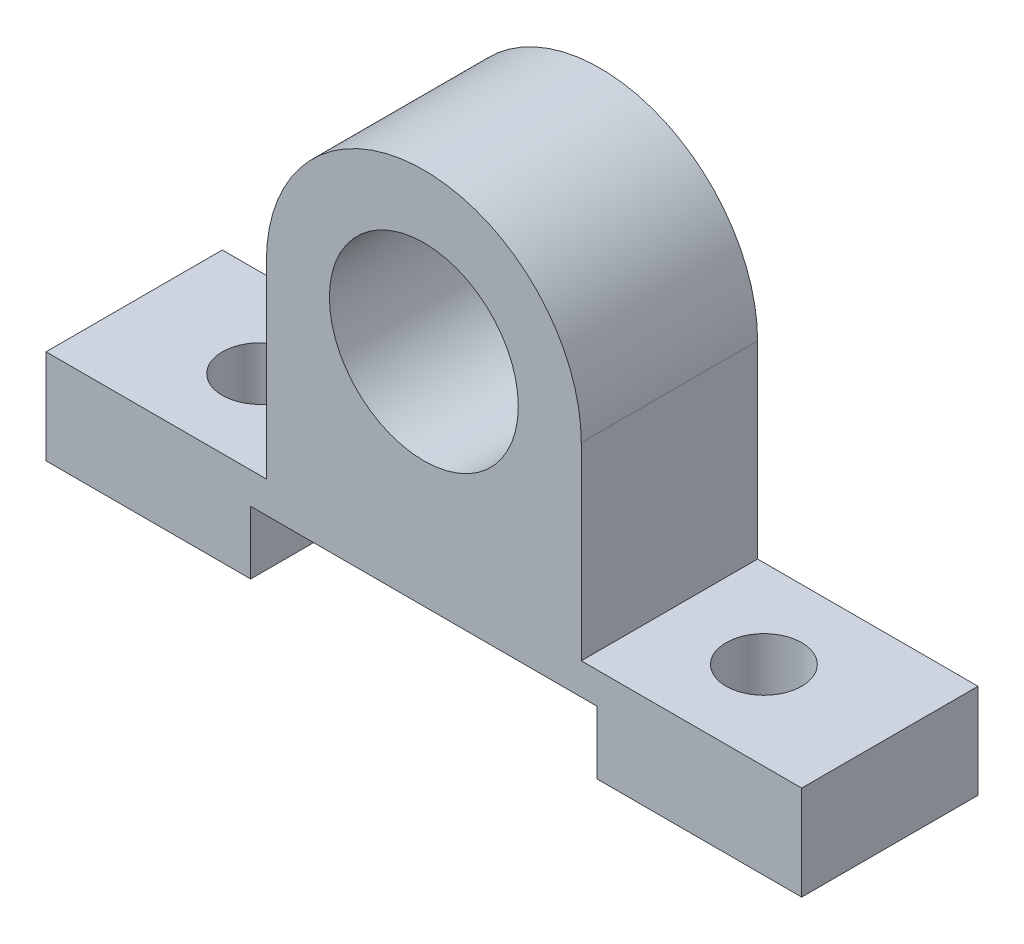
SolidWorks part; units mm, degrees
ref_plane "Front Plane" through (0, 0, 0) normal (0, 0, 1) x (1, 0, 0)
ref_plane "Top Plane" through (0, 0, 0) normal (0, 1, 0) x (1, 0, 0)
ref_plane "Right Plane" through (0, 0, 0) normal (1, 0, 0) x (0, 0, -1)
sketch "Sketch2" plane through (0, 0, 0) normal (0, 0, 1) x (1, 0, 0)
  line L0 (34.925, 0) -> (76.2, 0)
  line L1 (83.82, 0) -> (-83.82, 0) construction
  line L2 (76.2, 0) -> (76.2, 19.05)
  line L3 (76.2, 19.05) -> (31.75, 19.05)
  line L4 (31.75, 19.05) -> (31.75, 57.15)
  line L5 (0, -54.5101) -> (0, 54.5101) construction
  line L6 (34.925, 0) -> (34.925, 12.7)
  line L7 (34.925, 12.7) -> (-34.925, 12.7)
  line L8 (-76.2, 0) -> (-76.2, 19.05)
  line L9 (-34.925, 0) -> (-34.925, 12.7)
  line L10 (-31.75, 19.05) -> (-31.75, 57.15)
  line L11 (-76.2, 19.05) -> (-31.75, 19.05)
  line L12 (-34.925, 0) -> (-76.2, 0)
  arc A0 (31.75, 57.15) -> (-31.75, 57.15) centre (0, 57.15) ccw
  circle A1 centre (0, 57.15) radius 19.05
  point P15 (0, 12.7)
  dimension "D6" = 31.75
  dimension "D7" = 38.1
  dimension "D1" = 19.05
  dimension "D2" = 76.2
  dimension "D3" = 12.7
  dimension "D4" = 34.925
  dimension "D5" = 38.1
extrude "Boss-Extrude1" add sketch "Sketch2" along normal mid plane 35.56
sketch "Sketch3" plane through (0, 19.05, 0) normal (0, 1, 0) x (1, 0, 0)
  line L0 (-48.895, 0) -> (48.895, 0) construction
  line L1 (0, -19.558) -> (0, 19.558) construction
  circle A0 centre (-50.8, 0) radius 7.62
  circle A1 centre (50.8, 0) radius 7.62
  dimension "D3" = 15.24
  dimension "D4" = 15.24
  dimension "D1" = 101.6
  dimension "D2" = 50.8
extrude "Cut-Extrude1" cut sketch "Sketch3" against normal through all
